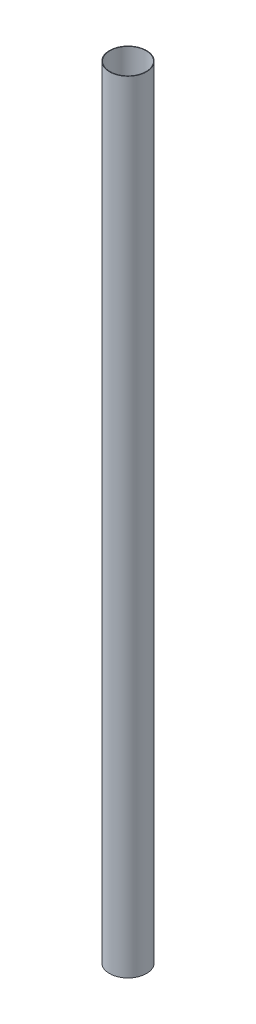
SolidWorks part; units mm, degrees
ref_plane "Front" through (0, 0, 0) normal (0, 0, 1) x (1, 0, 0)
ref_plane "Top" through (0, 0, 0) normal (0, 1, 0) x (1, 0, 0)
ref_plane "Right" through (0, 0, 0) normal (1, 0, 0) x (0, 0, -1)
sketch "Sketch1" plane through (0, 0, 0) normal (0, 0, 1) x (1, 0, 0)
  line L0 (0, 0) -> (1900, 0) construction
  line L1 (1900, 0) -> (444.5156, 1221.2965) construction
  line L2 (1900, 0) -> (7.2301, -165.5959) construction
  line L3 (1900, 0) -> (3355.4844, 1221.2965) construction
  line L5 (3800, 0) -> (1900, 0) construction
  line L6 (1900, 0) -> (3355.4844, -1221.2965) construction
  line L7 (3355.4844, 1221.2965) -> (3355.4844, -1221.2965) construction
  line L8 (0, 0) -> (0, 3200)
  arc A2 (3355.4844, -1221.2965) -> (3355.4844, 1221.2965) centre (1900, 0) ccw construction
  dimension "D1" = 3200
  dimension "D2" = 40
  dimension "D3" = 5
  dimension "D4" = 80
  dimension "D5" = 40
  dimension "D6" = 2442.5929
  dimension "D7" = 444.5156
  dimension "D8" = 1221.2965
sketch "Sketch2" plane through (0, 0, 0) normal (0, 1, 0) x (1, 0, 0)
  circle A0 centre (0, 0) radius 76
  circle A1 centre (0, 0) radius 74
  dimension "D1" = 152
  dimension "D2" = 148
sweep "Sweep1" add profiles "Sketch2" path "Sketch1"
